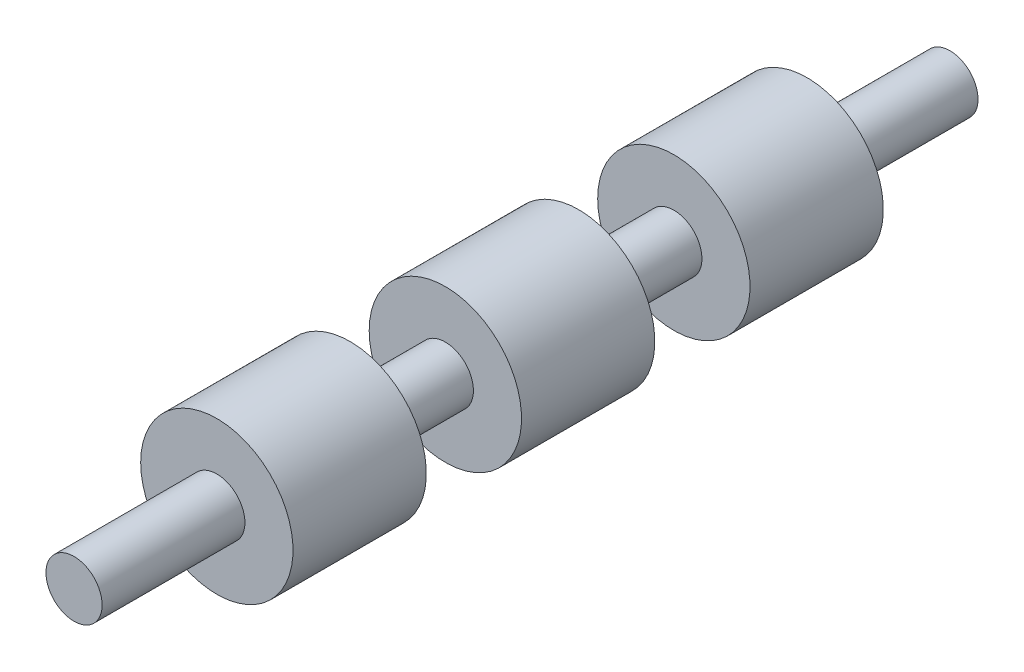
SolidWorks part; units mm, degrees
ref_plane "Alzado" through (0, 0, 0) normal (0, 0, 1) x (1, 0, 0)
ref_plane "Planta" through (0, 0, 0) normal (0, 1, 0) x (1, 0, 0)
ref_plane "Vista lateral" through (0, 0, 0) normal (1, 0, 0) x (0, 0, -1)
sketch "Croquis1" plane through (0, 0, 0) normal (0, 0, 1) x (1, 0, 0)
  circle A0 centre (0, 0) radius 2.95
  dimension "D1" = 5.9
extrude "Saliente-Extruir1" add sketch "Croquis1" along normal blind 15
sketch "Croquis2" plane through (0, 0, 0) normal (0, 0, -1) x (-1, 0, 0)
  circle A0 centre (0, 0) radius 8
  dimension "D1" = 16
extrude "Saliente-Extruir2" add sketch "Croquis2" along normal blind 14
sketch "Croquis3" plane through (0, 0, -14) normal (0, 0, -1) x (-1, 0, 0)
  circle A0 centre (0, 0) radius 2.95
  dimension "D1" = 5.9
extrude "Saliente-Extruir3" add sketch "Croquis3" along normal blind 10
sketch "Croquis4" plane through (0, 0, -24) normal (0, 0, -1) x (-1, 0, 0)
  circle A0 centre (0, 0) radius 8
  dimension "D1" = 16
extrude "Saliente-Extruir4" add sketch "Croquis4" along normal blind 14
sketch "Croquis5" plane through (0, 0, -38) normal (0, 0, -1) x (-1, 0, 0)
  circle A0 centre (0, 0) radius 2.95
  dimension "D1" = 5.9
extrude "Saliente-Extruir5" add sketch "Croquis5" along normal blind 10
sketch "Croquis6" plane through (0, 0, -48) normal (0, 0, -1) x (-1, 0, 0)
  circle A0 centre (0, 0) radius 8
  dimension "D1" = 16
extrude "Saliente-Extruir6" add sketch "Croquis6" along normal blind 14
sketch "Croquis7" plane through (0, 0, -62) normal (0, 0, -1) x (-1, 0, 0)
  circle A0 centre (0, 0) radius 2.95
  dimension "D1" = 5.9
extrude "Saliente-Extruir7" add sketch "Croquis7" along normal blind 15
